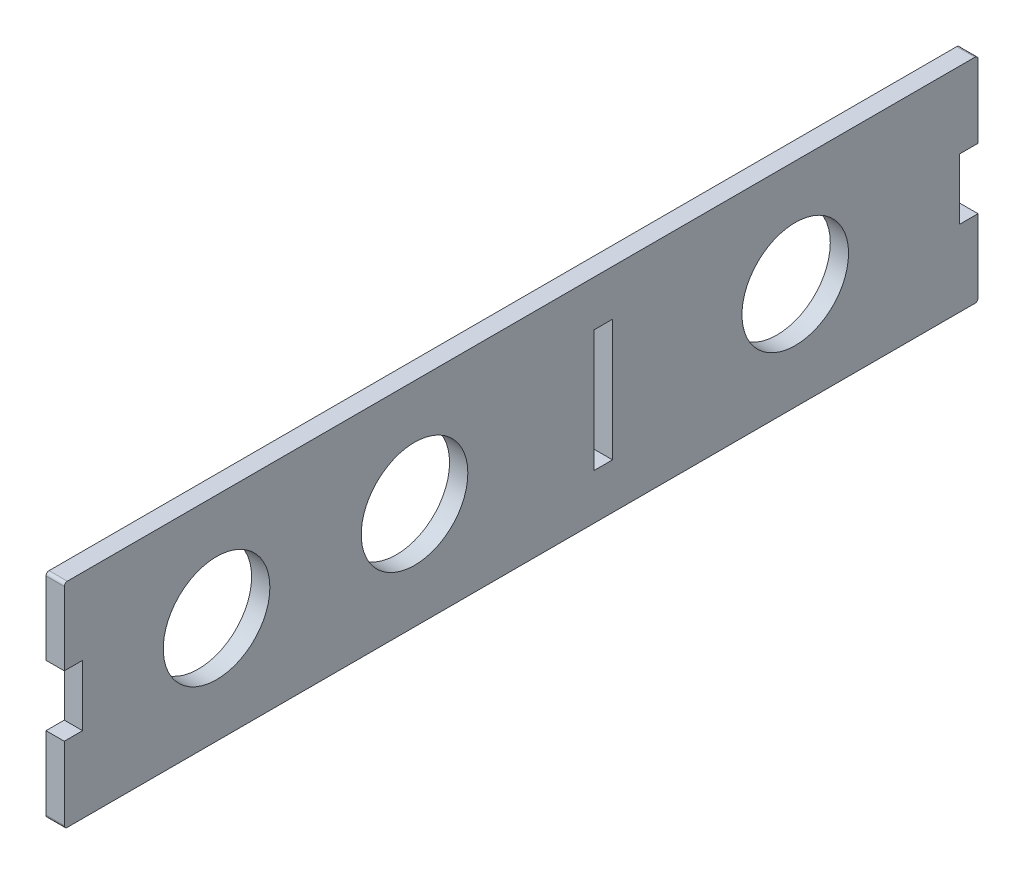
SolidWorks part; units mm, degrees
material "Beech"
ref_plane "Спереди" through (0, 0, 0) normal (0, 0, 1) x (1, 0, 0)
ref_plane "Сверху" through (0, 0, 0) normal (0, 1, 0) x (1, 0, 0)
ref_plane "Справа" through (0, 0, 0) normal (1, 0, 0) x (0, 0, -1)
sketch "Sketch1" plane through (0, 0, 0) normal (1, 0, 0) x (0, 0, -1)
  line L1 (0, 0) -> (300, 0)
  line L2 (0, 0) -> (0, 70)
  line L3 (0, 70) -> (300, 70)
  line L4 (300, 0) -> (300, 70)
  dimension "D1" = 70
  dimension "D2" = 300
extrude "wall" add sketch "Sketch1" along normal blind 6
sketch "Sketch2" plane through (6, 0, 0) normal (1, 0, 0) x (0, 0, -1)
  line L0 (0, 45) -> (6, 45)
  line L1 (0, 70) -> (0, 0) construction
  line L2 (6, 45) -> (6, 25)
  line L3 (6, 25) -> (0, 25)
  line L4 (300, 45) -> (294, 45)
  line L5 (300, 0) -> (300, 70) construction
  line L6 (294, 45) -> (294, 25)
  line L7 (294, 25) -> (300, 25)
  line L8 (174, 55) -> (174, 15)
  line L9 (174, 15) -> (180, 15)
  line L10 (180, 15) -> (180, 55)
  line L11 (174, 55) -> (180, 55)
  line L16 (0, 0) -> (300, 0) construction
  point P32 (174, 35)
  point P36 (6, 35)
  dimension "D1" = 6
  dimension "D3" = 20
  dimension "D4" = 35
  dimension "D6" = 40
  dimension "D7" = 6
  dimension "D8" = 120
  dimension "D9" = 35
extrude "mount" cut sketch "Sketch2" against normal through all
sketch "Sketch3" plane through (6, 0, 0) normal (1, 0, 0) x (0, 0, -1)
  line L0 (300, 0) -> (300, 25) construction
  line L1 (0, 25) -> (0, 0) construction
  line L2 (0, 0) -> (300, 0) construction
  circle A0 centre (50, 35) radius 17.5
  circle A1 centre (115, 35) radius 17.5
  circle A2 centre (240, 35) radius 17.5
  dimension "D1" = 35
  dimension "D2" = 65
  dimension "D3" = 60
  dimension "D4" = 50
  dimension "D5" = 35
extrude "lite" cut sketch "Sketch3" against normal through all
fillet "fillet" radius 1 4 edges at (3, 0, -300) (3, 70, -300) (3, 0, 0) (3, 70, 0)
